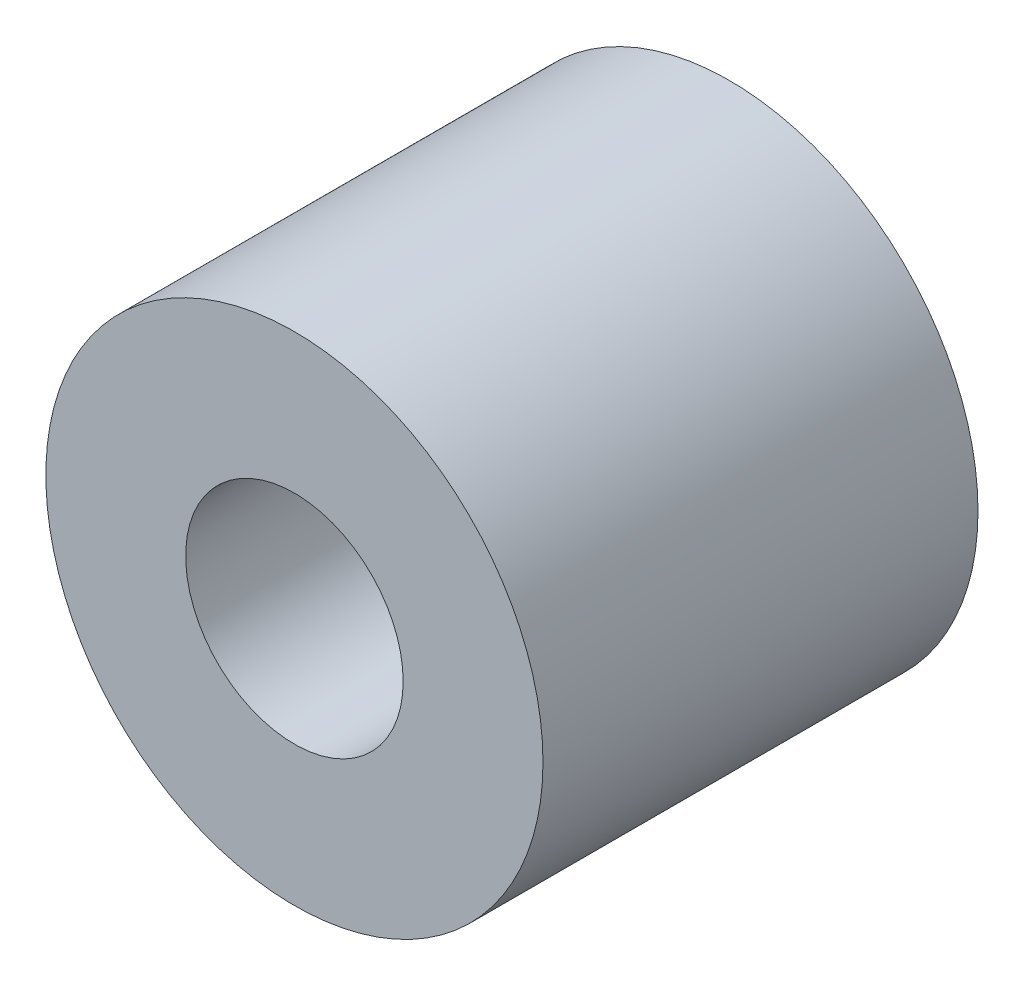
SolidWorks part; units mm, degrees
ref_plane "Front Plane" through (0, 0, 0) normal (0, 0, 1) x (1, 0, 0)
ref_plane "Top Plane" through (0, 0, 0) normal (0, 1, 0) x (1, 0, 0)
ref_plane "Right Plane" through (0, 0, 0) normal (1, 0, 0) x (0, 0, -1)
sketch "Sketch1" plane through (0, 0, 0) normal (0, 0, 1) x (1, 0, 0)
  circle A0 centre (0, 0) radius 1.75
  circle A1 centre (0, 0) radius 4
  dimension "D1" = 3.5
  dimension "D2" = 8
extrude "Boss-Extrude1" add sketch "Sketch1" along normal blind 7
